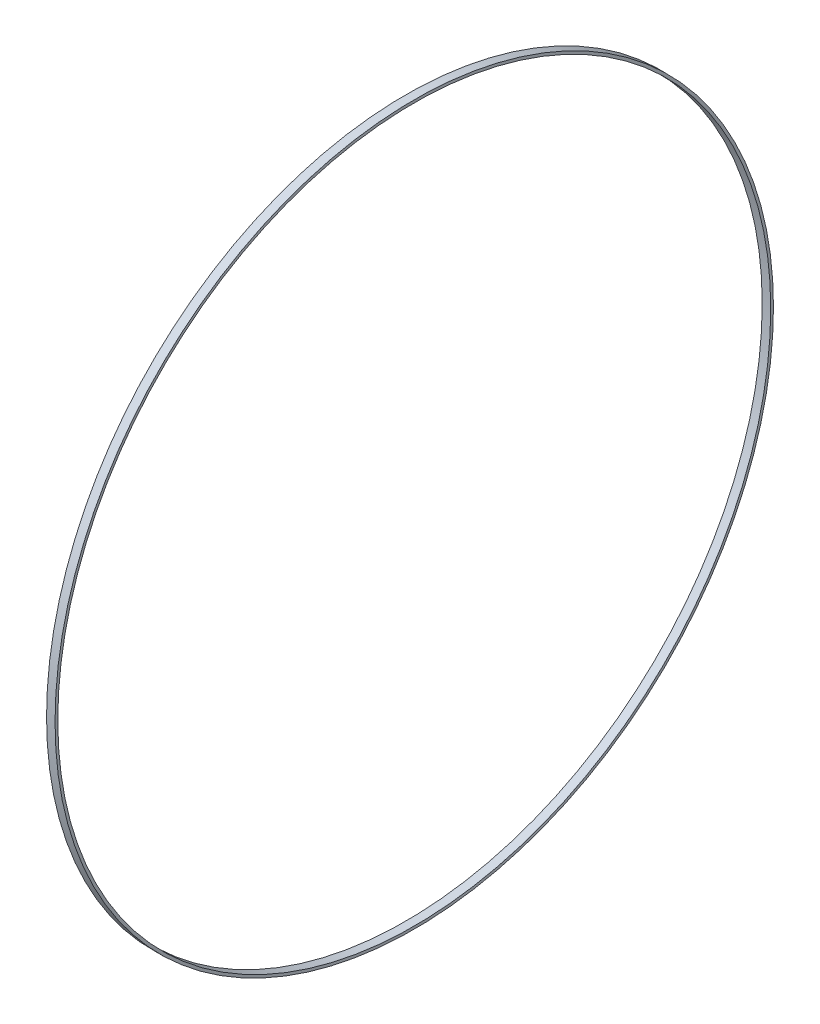
SolidWorks part; units mm, degrees
material "ASTM A36 Steel"
ref_plane "Front Plane" through (0, 0, 0) normal (0, 0, 1) x (1, 0, 0)
ref_plane "Top Plane" through (0, 0, 0) normal (0, 1, 0) x (1, 0, 0)
ref_plane "Right Plane" through (0, 0, 0) normal (1, 0, 0) x (0, 0, -1)
sketch "Sketch1" plane through (0, 0, 0) normal (1, 0, 0) x (0, 0, -1)
  circle A0 centre (0, 0) radius 1055
  circle A1 centre (0, 0) radius 1047
  dimension "D1" = 2094
  dimension "D2" = 8
extrude "Boss-Extrude1" add sketch "Sketch1" along normal blind 25
